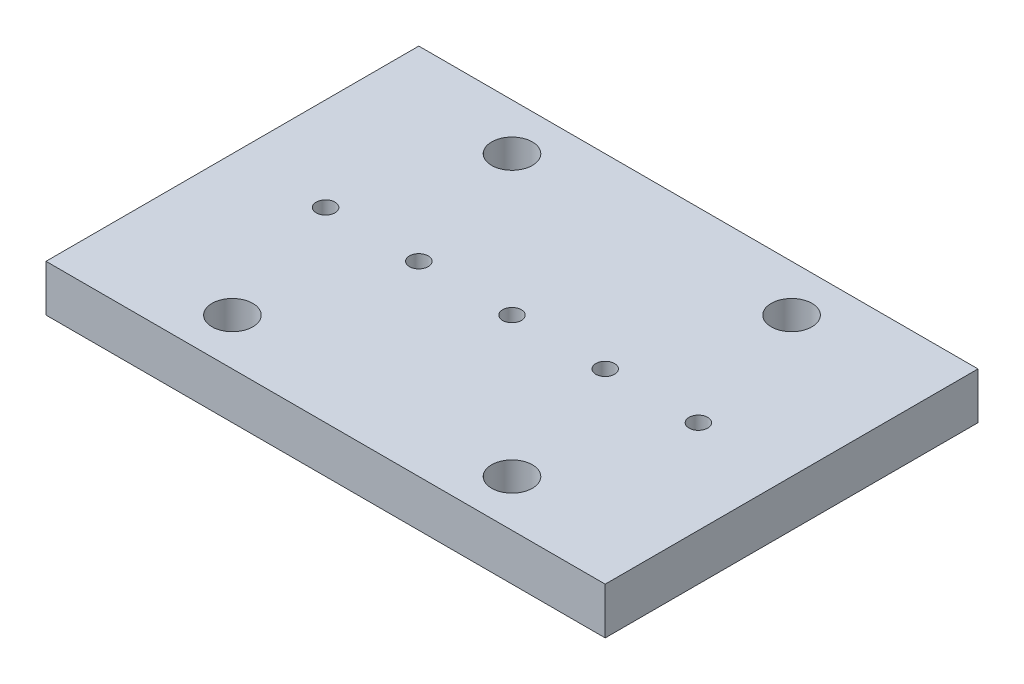
SolidWorks part; units mm, degrees
ref_plane "Front Plane" through (0, 0, 0) normal (0, 0, 1) x (1, 0, 0)
ref_plane "Top Plane" through (0, 0, 0) normal (0, 1, 0) x (1, 0, 0)
ref_plane "Right Plane" through (0, 0, 0) normal (1, 0, 0) x (0, 0, -1)
sketch "Sketch1" plane through (0, 0, 0) normal (0, 1, 0) x (1, 0, 0)
  line L1 (-76.2, -50.8) -> (76.2, -50.8)
  line L2 (-76.2, -50.8) -> (-76.2, 50.8)
  line L3 (-76.2, 50.8) -> (76.2, 50.8)
  line L4 (76.2, -50.8) -> (76.2, 50.8)
  line L5 (-76.2, -50.8) -> (76.2, 50.8) construction
  line L6 (-76.2, 50.8) -> (76.2, -50.8) construction
  point P0 (0, 0)
  dimension "D1" = 152.4
  dimension "D2" = 101.6
extrude "Boss-Extrude1" add sketch "Sketch1" along normal blind 12.7
hole_wizard "CBORE for 1/4 Socket Head Cap Screw1" positions "Sketch2" profile "Sketch3" counterbore size "1/4" standard "ANSI Inch" end condition through all
sketch "Sketch2" plane through (0, 12.7, 0) normal (0, 1, 0) x (1, 0, 0)
  point P0 (-38.1, 38.1)
  point P7 (38.1, 38.1)
  point P8 (38.1, -38.1)
  point P9 (-38.1, -38.1)
  dimension "D1" = 38.1
  dimension "D2" = 38.1
  dimension "D3" = 2
  dimension "D4" = 2
sketch "Sketch3" plane through (-38.1, 12.7, -38.1) normal (1, 0, 0) x (0, 0, 1)
  line L0 (0, 0) -> (0, 12.7)
  line L1 (0, 12.7) -> (3.5712, 12.7)
  line L3 (3.5712, 12.7) -> (3.5712, 8.89)
  line L4 (3.5712, 8.89) -> (5.5562, 8.89)
  line L5 (5.5562, 8.89) -> (5.5562, 0)
  line L7 (5.5562, 0) -> (0, 0)
  line L11 (0, -6.35) -> (0, 107.95) construction
  dimension "Thru Hole Dia." = 7.1425
  dimension "Thru Hole Depth" = 12.7
  dimension "C'Bore Dia." = 11.1125
  dimension "C'Bore Depth" = 8.89
hole_wizard "Tap Drill for 1/4-20 Tap1" positions "Sketch4" profile "Sketch5" hole size "1/4-20" standard "ANSI Inch" end condition through all
sketch "Sketch4" plane through (0, 12.7, 0) normal (0, 1, 0) x (1, 0, 0)
  point P0 (0, 0)
  point P7 (25.4, 0)
  point P8 (50.8, 0)
  point P11 (-25.4, 0)
  point P12 (-50.8, 0)
  dimension "D1" = 3
  dimension "D2" = 3
sketch "Sketch5" plane through (0, 12.7, 0) normal (1, 0, 0) x (0, 0, 1)
  line L0 (0, 0) -> (0, 12.7)
  line L1 (0, 12.7) -> (2.5527, 12.7)
  line L2 (2.5527, 12.7) -> (2.5527, 0)
  line L5 (2.5527, 0) -> (0, 0)
  line L11 (0, -6.35) -> (0, 107.95) construction
  dimension "Thru Hole Dia." = 5.1054
  dimension "Thru Hole Depth" = 12.7
